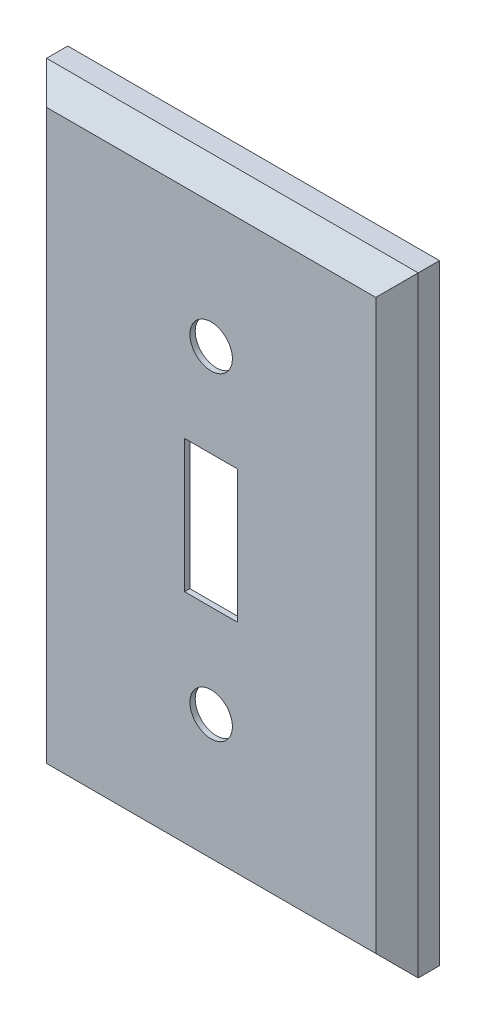
SolidWorks part; units mm, degrees
ref_plane "Alzado" through (0, 0, 0) normal (0, 0, 1) x (1, 0, 0)
ref_plane "Planta" through (0, 0, 0) normal (0, 1, 0) x (1, 0, 0)
ref_plane "Vista lateral" through (0, 0, 0) normal (1, 0, 0) x (0, 0, -1)
sketch "Croquis1" plane through (0, 0, 0) normal (0, 0, 1) x (1, 0, 0)
  line L1 (-35, -57.5) -> (35, -57.5)
  line L2 (-35, -57.5) -> (-35, 57.5)
  line L3 (-35, 57.5) -> (35, 57.5)
  line L4 (35, -57.5) -> (35, 57.5)
  line L5 (-35, -57.5) -> (35, 57.5) construction
  line L6 (-35, 57.5) -> (35, -57.5) construction
  point P0 (0, 0)
  dimension "D1" = 70
  dimension "D2" = 115
extrude "Saliente-Extruir1" add sketch "Croquis1" along normal blind 8
chamfer "Chaflán1" distance 4 angle 45 4 edges at (0, -57.5, 8) (-35, 0, 8) (0, 57.5, 8) (35, 0, 8)
shell "Vaciado1" thickness 1
sketch "Croquis2" plane through (0, 0, 8) normal (0, 0, 1) x (1, 0, 0)
  line L1 (-5, -12.5) -> (5, -12.5)
  line L2 (-5, -12.5) -> (-5, 12.5)
  line L3 (-5, 12.5) -> (5, 12.5)
  line L4 (5, -12.5) -> (5, 12.5)
  line L5 (-5, -12.5) -> (5, 12.5) construction
  line L6 (-5, 12.5) -> (5, -12.5) construction
  circle A0 centre (0, 30) radius 4
  circle A1 centre (0, -30) radius 4
  point P0 (0, 0)
  point P10 (0, -12.5)
  dimension "D3" = 8
  dimension "D4" = 17.5
  dimension "D5" = 17.5
  dimension "D1" = 10
  dimension "D2" = 25
extrude "Cortar-Extruir1" cut sketch "Croquis2" against normal through all
